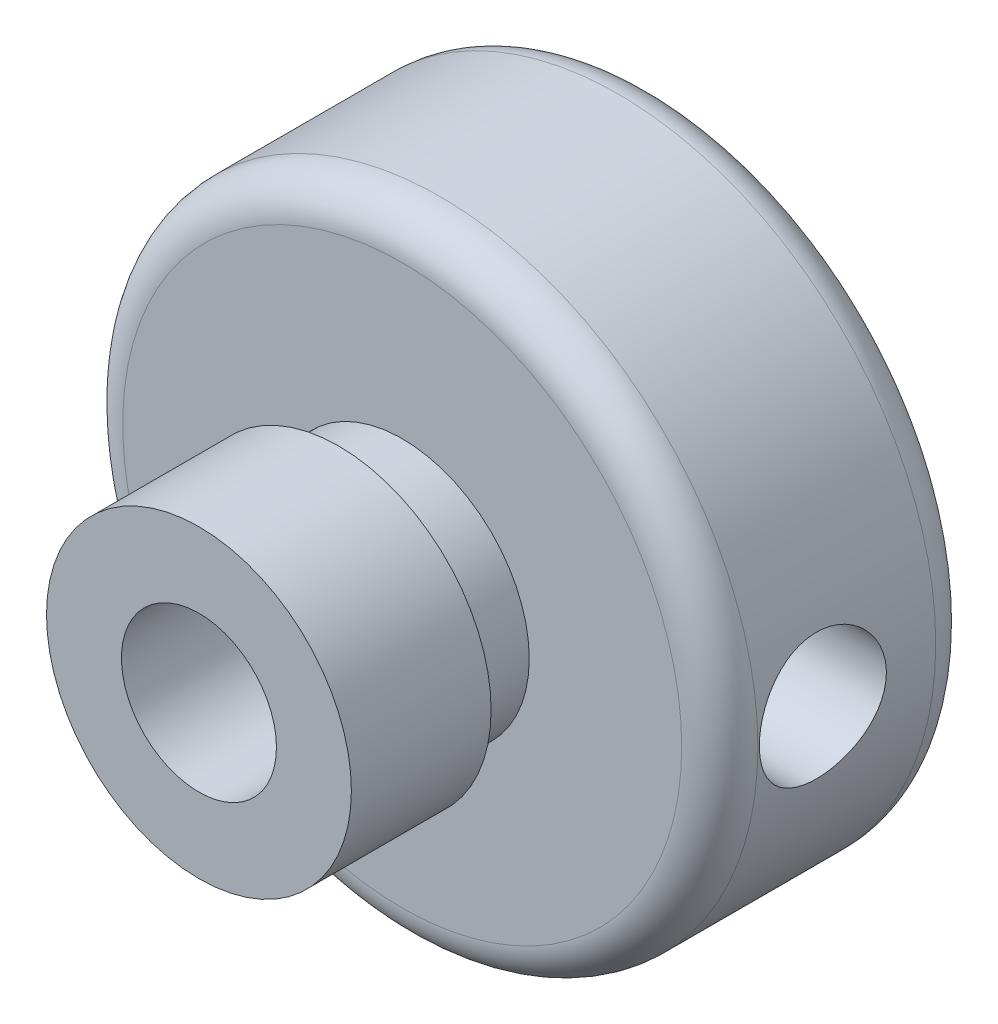
SolidWorks part; units mm, degrees
ref_plane "Plan1" through (0, 0, 0) normal (0, 0, 1) x (1, 0, 0)
ref_plane "Plan2" through (0, 0, 0) normal (0, 1, 0) x (1, 0, 0)
ref_plane "Plan3" through (0, 0, 0) normal (1, 0, 0) x (0, 0, -1)
sketch "Esquisse1" plane through (0, 0, 0) normal (0, 0, 1) x (1, 0, 0)
  circle A0 centre (0, 0) radius 12.5
  dimension "D1" = 25
extrude "Base-Extrusion" add sketch "Esquisse1" along normal blind 10
sketch "Esquisse2" plane through (0, 0, 10) normal (0, 0, 1) x (1, 0, 0)
  circle A0 centre (0, 0) radius 6
  dimension "D1" = 12
extrude "Boss.-Extru.1" add sketch "Esquisse2" along normal blind 8
sketch "Esquisse3" plane through (0, 0, 18) normal (0, 0, 1) x (1, 0, 0)
  circle A0 centre (0, 0) radius 3.05
  dimension "D1" = 6.1
extrude "Enlèv. mat.-Extru.1" cut sketch "Esquisse3" against normal through all
sketch "Esquisse4" plane through (0, 0, 0) normal (0, 0, -1) x (-1, 0, 0)
  circle A0 centre (0, 0) radius 5
  dimension "D1" = 10
extrude "Enlèv. mat.-Extru.2" cut sketch "Esquisse4" against normal blind 8
sketch "Esquisse5" plane through (0, 0, 0) normal (1, 0, 0) x (0, 0, -1)
  line L0 (-21.3998, 0) -> (3.3457, 0) construction
  line L1 (-8, 0) -> (-18, 0) construction
  line L2 (-10, 7) -> (-12.5, 7)
  line L3 (-10, 7) -> (-10, 5)
  line L4 (-12.5, 5) -> (-10, 5)
  line L5 (-12.5, 5) -> (-12.5, 7)
  line L6 (-10, 12.5) -> (-10, -12.5) construction
  line L7 (-18, 6) -> (-18, -6) construction
  dimension "D1" = 5.5
revolve "Enlever de la matière-Révolution1" cut sketch "Esquisse5" angle 360 about L0
fillet "Congé1" radius 1.5
ref_plane "Plan4" through (12.5, 0, 0) normal (1, 0, 0) x (0, 0, -1)
sketch "Esquisse7" plane through (12.5, 0, 0) normal (1, 0, 0) x (0, 0, -1)
  line L0 (-8, 0) -> (-18, 0) construction
  circle A0 centre (-5.9424, 0) radius 2.5
  dimension "D1" = 5
extrude "Enlèv. mat.-Extru.4" cut sketch "Esquisse7" against normal blind 8
sketch "Esquisse9" plane through (0, 0, 10) normal (0, 0, 1) x (1, 0, 0)
  point P0 (0, 0)
